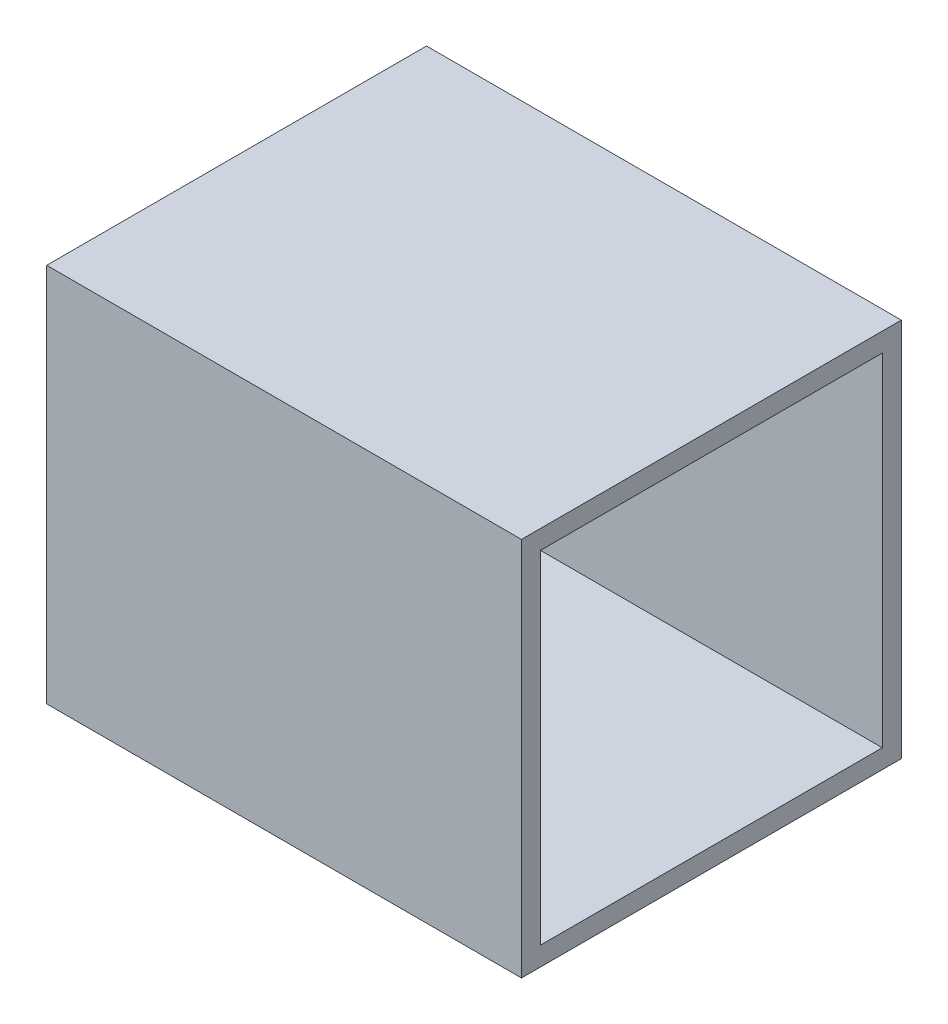
SolidWorks part; units mm, degrees
ref_plane "Front Plane" through (0, 0, 0) normal (0, 0, 1) x (1, 0, 0)
ref_plane "Top Plane" through (0, 0, 0) normal (0, 1, 0) x (1, 0, 0)
ref_plane "Right Plane" through (0, 0, 0) normal (1, 0, 0) x (0, 0, -1)
sketch "Sketch1" plane through (0, 0, 0) normal (1, 0, 0) x (0, 0, -1)
  line L2 (254, 254) -> (0, 254)
  line L3 (254, 254) -> (254, 0)
  line L4 (254, 0) -> (0, 0)
  line L5 (0, 254) -> (0, 0)
  dimension "D1" = 254
  dimension "D2" = 254
extrude "Boss-Extrude1" add sketch "Sketch1" along normal blind 12.7
sketch "Sketch2" plane through (12.7, 0, 0) normal (1, 0, 0) x (0, 0, -1)
  line L0 (241.3, 12.7) -> (241.3, 241.3)
  line L1 (241.3, 241.3) -> (12.7, 241.3)
  line L2 (12.7, 241.3) -> (12.7, 12.7)
  line L3 (12.7, 12.7) -> (241.3, 12.7)
  line L4 (254, 0) -> (254, 254)
  line L5 (254, 254) -> (0, 254)
  line L6 (0, 254) -> (0, 0)
  line L7 (0, 0) -> (254, 0)
  line L8 (254, 0) -> (254, 254)
  line L9 (254, 254) -> (0, 254)
  line L10 (0, 254) -> (0, 0)
  line L11 (0, 0) -> (254, 0)
  dimension "D1" = 0
  dimension "D2" = 12.7
extrude "Boss-Extrude2" add sketch "Sketch2" along normal blind 304.8
